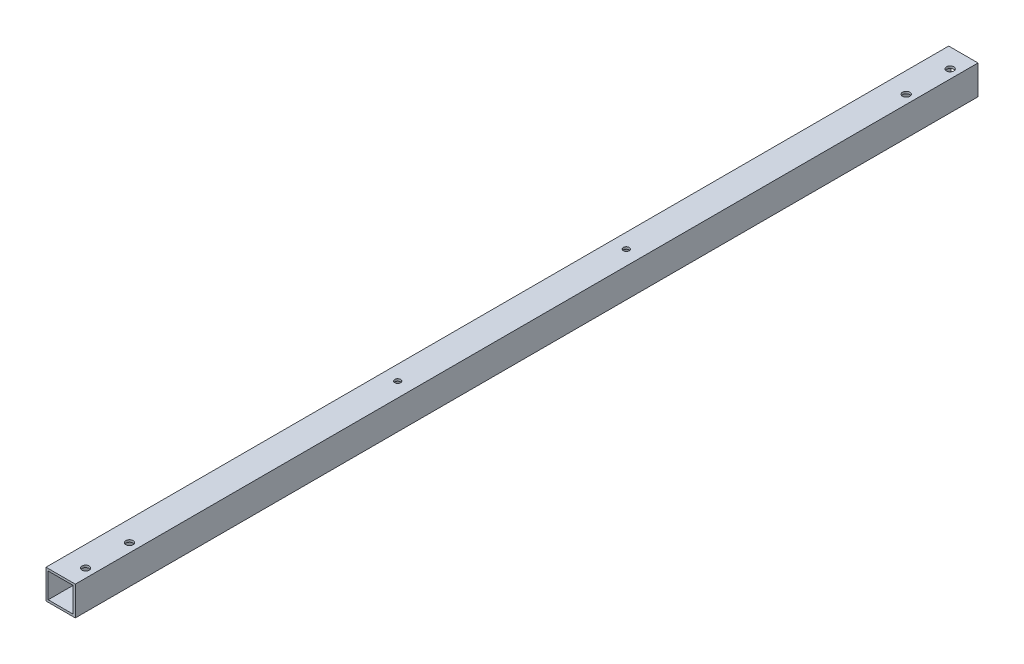
SolidWorks part; units mm, degrees
material "6061 合金"
ref_plane "前视基准面" through (0, 0, 0) normal (0, 0, 1) x (1, 0, 0)
ref_plane "上视基准面" through (0, 0, 0) normal (0, 1, 0) x (1, 0, 0)
ref_plane "右视基准面" through (0, 0, 0) normal (1, 0, 0) x (0, 0, -1)
sketch "草图1" plane through (0, 0, 0) normal (0, 0, 1) x (1, 0, 0)
  line L1 (-10, 10) -> (10, 10)
  line L2 (-10, 10) -> (-10, -10)
  line L3 (-10, -10) -> (10, -10)
  line L4 (10, 10) -> (10, -10)
  line L5 (-10, 10) -> (10, -10) construction
  line L6 (-10, -10) -> (10, 10) construction
  line L7 (-8.5, 8.5) -> (8.5, 8.5)
  line L8 (-8.5, 8.5) -> (-8.5, -8.5)
  line L9 (-8.5, -8.5) -> (8.5, -8.5)
  line L10 (8.5, 8.5) -> (8.5, -8.5)
  line L11 (-8.5, 8.5) -> (8.5, -8.5) construction
  line L12 (-8.5, -8.5) -> (8.5, 8.5) construction
  point P0 (0, 0)
  point P5 (0, 0)
  dimension "D1" = 20
  dimension "D2" = 20
  dimension "D3" = 17
  dimension "D4" = 17
extrude "凸台-拉伸1" add sketch "草图1" along normal blind 616
sketch "草图4" plane through (0, -10, 0) normal (0, -1, 0) x (1, 0, 0)
  line L0 (10, 616) -> (10, 0) construction
  line L2 (11, 0) -> (-11, 0) construction
  line L3 (-10, 616) -> (10, 616) construction
  circle A0 centre (4, 13) radius 2.5
  circle A1 centre (4, 43) radius 2.5
  circle A2 centre (4, 603) radius 2.5
  circle A3 centre (4, 573) radius 2.5
  dimension "D1" = 6
  dimension "D3" = 30
  dimension "D4" = 30
  dimension "D6" = 5
  dimension "D7" = 5
  dimension "D8" = 5
  dimension "D9" = 5
  dimension "D2" = 13
  dimension "D5" = 13
extrude "切除-拉伸3" cut sketch "草图4" against normal blind 20
sketch "草图5" plane through (0, -10, 0) normal (0, -1, 0) x (1, 0, 0)
  line L0 (0, -11) -> (0, 11) construction
  line L1 (11, 0) -> (-11, 0) construction
  line L2 (-10, 616) -> (10, 616) construction
  circle A0 centre (0, 230) radius 2
  circle A1 centre (0, 386) radius 2
  dimension "D1" = 230
  dimension "D2" = 230
extrude "切除-拉伸4" cut sketch "草图5" against normal blind 20
